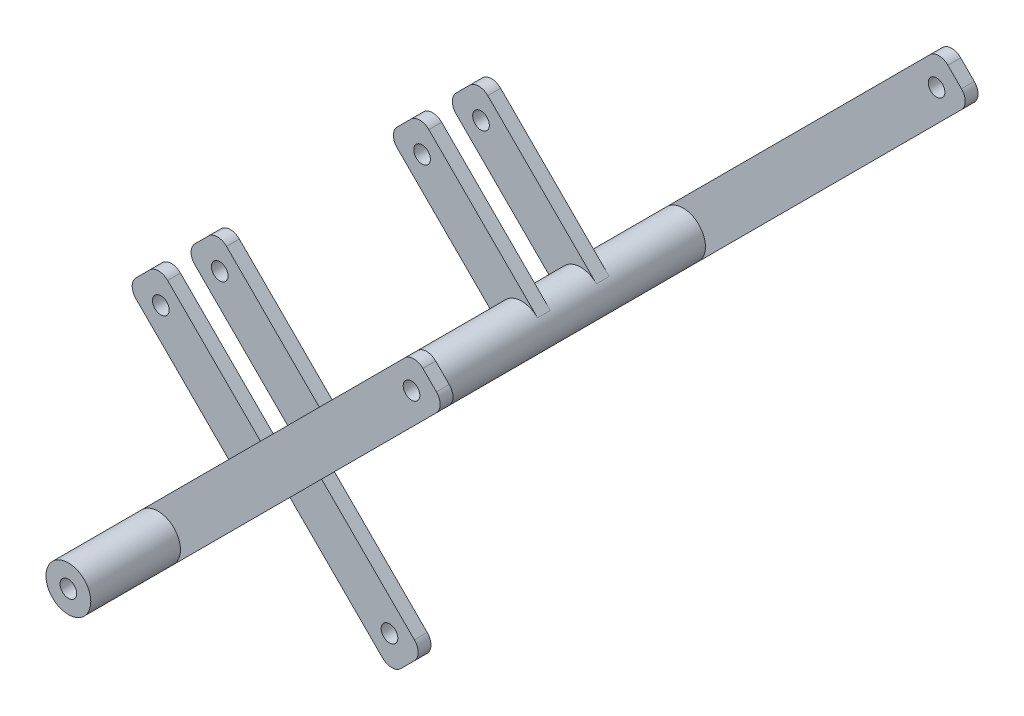
SolidWorks part; units mm, degrees
ref_plane "Front Plane" through (0, 0, 0) normal (0, 0, 1) x (1, 0, 0)
ref_plane "Top Plane" through (0, 0, 0) normal (0, 1, 0) x (1, 0, 0)
ref_plane "Right Plane" through (0, 0, 0) normal (1, 0, 0) x (0, 0, -1)
sketch "Sketch1" plane through (0, 0, 0) normal (0, 0, 1) x (1, 0, 0)
  circle A0 centre (0, 0) radius 17.5
  circle A1 centre (0, 0) radius 6.5
  dimension "D1" = 35
  dimension "D2" = 13
extrude "Boss-Extrude1" add sketch "Sketch1" along normal mid plane 560
ref_plane "Plane1" through (0, 0, 210) normal (0, 0, 1) x (1, 0, 0)
sketch "Sketch2" plane through (0, 0, 210) normal (0, 0, 1) x (1, 0, 0)
  line L0 (-12.3744, 12.3744) -> (192.6866, 217.4353)
  line L1 (206.8287, 217.4353) -> (217.4353, 206.8287)
  line L2 (217.4353, 192.6866) -> (12.3744, -12.3744)
  line L3 (0, 17.5) -> (-154.2118, 17.5) construction
  line L4 (212.132, 212.132) -> (197.9899, 197.9899) construction
  circle A0 centre (0, 0) radius 17.5 construction
  arc A1 (12.3744, -12.3744) -> (-12.3744, 12.3744) centre (0, 0) ccw
  circle A2 centre (197.9899, 197.9899) radius 6.5
  arc A3 (217.4353, 206.8287) -> (217.4353, 192.6866) centre (210.3643, 199.7577) cw
  arc A4 (206.8287, 217.4353) -> (192.6866, 217.4353) centre (199.7577, 210.3643) ccw
  point P13 (224.5064, 199.7577)
  point P16 (199.7577, 224.5064)
  dimension "D4" = 13
  dimension "D6" = 10
  dimension "D1" = 35
  dimension "D2" = 300
  dimension "D3" = 135
  dimension "D5" = 20
extrude "Boss-Extrude2" add sketch "Sketch2" against normal blind 10
mirror "Mirror1" about plane through (0, 0, 0) normal (0, 0, 1) of "Boss-Extrude2"
ref_plane "Plane2" through (0, 0, 130) normal (0, 0, 1) x (1, 0, 0)
sketch "Sketch3" plane through (0, 0, 130) normal (0, 0, 1) x (1, 0, 0)
  line L0 (0, 17.5) -> (240.4529, 17.5) construction
  line L1 (12.3744, 12.3744) -> (-72.4784, 97.2272)
  line L2 (-86.6206, 97.2272) -> (-97.2272, 86.6206)
  line L3 (-97.2272, 72.4784) -> (-12.3744, -12.3744)
  line L4 (-91.9239, 91.9239) -> (-77.7817, 77.7817) construction
  arc A0 (12.3744, -12.3744) -> (-12.3744, 12.3744) centre (0, 0) ccw construction
  circle A1 centre (0, 0) radius 17.5 construction
  arc A2 (12.3744, 12.3744) -> (-12.3744, -12.3744) centre (0, 0) ccw
  arc A3 (-72.4784, 97.2272) -> (-86.6206, 97.2272) centre (-79.5495, 90.1561) ccw
  arc A4 (-97.2272, 86.6206) -> (-97.2272, 72.4784) centre (-90.1561, 79.5495) ccw
  circle A5 centre (-77.7817, 77.7817) radius 6.5
  point P13 (-79.5495, 104.2983)
  point P16 (-104.2983, 79.5495)
  dimension "D4" = 10
  dimension "D5" = 13
  dimension "D1" = 35
  dimension "D2" = 135
  dimension "D3" = 130
  dimension "D6" = 20
extrude "Boss-Extrude3" add sketch "Sketch3" against normal blind 10
ref_plane "Plane3" through (0, 0, 102) normal (0, 0, -1) x (-1, 0, 0)
mirror "Mirror2" about plane through (0, 0, 102) normal (0, 0, -1) of "Boss-Extrude3"
mirror "Mirror3" about plane through (0, 0, 0) normal (0, 0, 1) of "Mirror2", "Boss-Extrude3"
sketch "Sketch4" plane through (0, 0, 102) normal (0, 0, -1) x (-1, 0, 0)
  line L0 (-12.3744, 12.3744) -> (-97.2272, -72.4784)
  line L1 (-97.2272, -86.6206) -> (-86.6206, -97.2272)
  line L2 (-72.4784, -97.2272) -> (12.3744, -12.3744)
  line L3 (97.2272, 72.4784) -> (12.3744, -12.3744) construction
  line L4 (-12.3744, 12.3744) -> (72.4784, 97.2272) construction
  line L5 (-91.9239, -91.9239) -> (-77.7817, -77.7817) construction
  arc A0 (12.3744, 12.3744) -> (-12.3744, -12.3744) centre (0, 0) ccw construction
  circle A1 centre (0, 0) radius 17.5 construction
  arc A2 (-86.6206, -97.2272) -> (-72.4784, -97.2272) centre (-79.5495, -90.1561) ccw
  arc A3 (-97.2272, -72.4784) -> (-97.2272, -86.6206) centre (-90.1561, -79.5495) ccw
  arc A4 (-12.3744, 12.3744) -> (12.3744, -12.3744) centre (0, 0) ccw
  circle A5 centre (-77.7817, -77.7817) radius 6.5
  dimension "D1" = 130
  dimension "D2" = 10
  dimension "D3" = 13
  dimension "D4" = 20
extrude "Boss-Extrude4" add sketch "Sketch4" along normal mid plane 10
